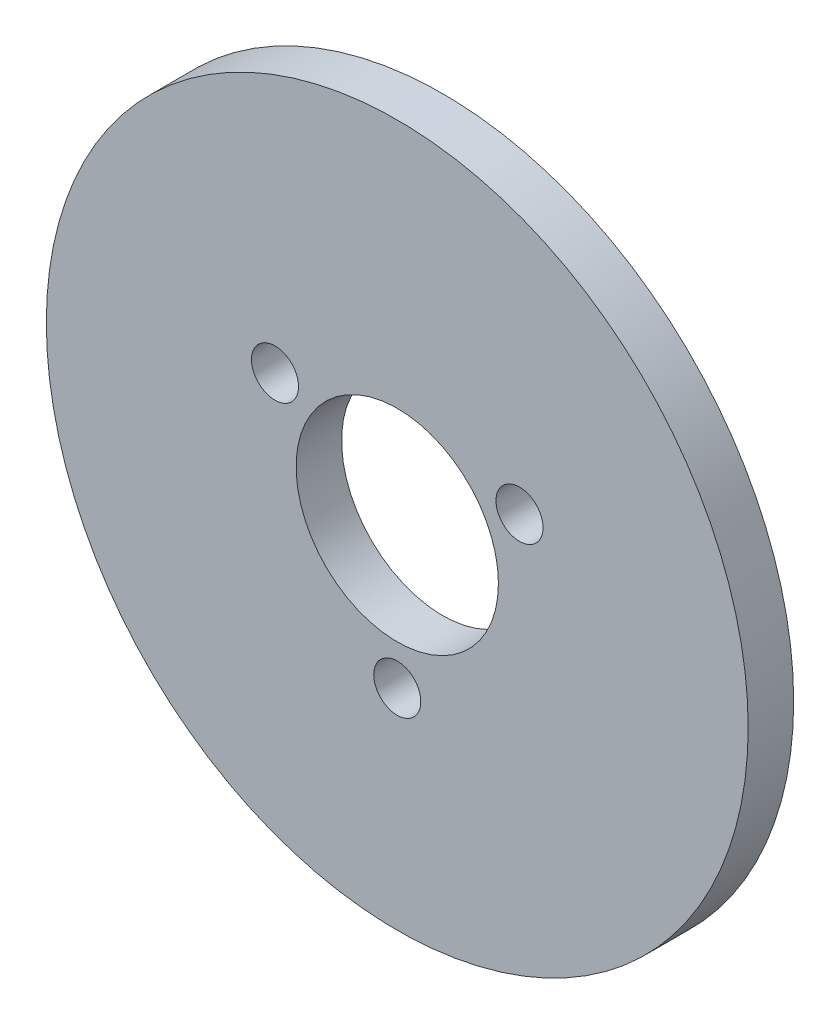
SolidWorks part; units mm, degrees
material "Acrylic (Medium-high impact)"
ref_plane "Front Plane" through (0, 0, 0) normal (0, 0, 1) x (1, 0, 0)
ref_plane "Top Plane" through (0, 0, 0) normal (0, 1, 0) x (1, 0, 0)
ref_plane "Right Plane" through (0, 0, 0) normal (1, 0, 0) x (0, 0, -1)
sketch "Sketch1" plane through (0, 0, 0) normal (0, 0, 1) x (1, 0, 0)
  circle A0 centre (0, 0) radius 22.375
  circle A1 centre (0, 0) radius 6.45
  dimension "D1" = 44.75
  dimension "D2" = 12.9
extrude "Boss-Extrude1" add sketch "Sketch1" along normal blind 2.9
sketch "Sketch2" plane through (0, 0, 0) normal (0, 0, -1) x (-1, 0, 0)
  circle A1 centre (7.7942, 4.5) radius 1.5
  circle A2 centre (7.7942, 4.5) radius 1.5
  circle A3 centre (-7.7942, 4.5) radius 1.5
  circle A4 centre (-7.7942, 4.5) radius 1.5
  circle A5 centre (0, -9) radius 1.5
  circle A6 centre (0, -9) radius 1.5
  dimension "D1" = 0
  dimension "D2" = 0
  dimension "D3" = 0
extrude "Cut-Extrude1" cut sketch "Sketch2" against normal through all
equation "\"smallPulleyTeeth\"= 15"
equation "\"largePulleyTeeth\"= 30"
equation "\"eighthThick\"= 2.9mm"
equation "\"sixteenthThick\"= 1.7mm"
equation "\"quarterThick\"=6.0mm"
equation "\"D1@Boss-Extrude1\"=\"eighthThick\""
